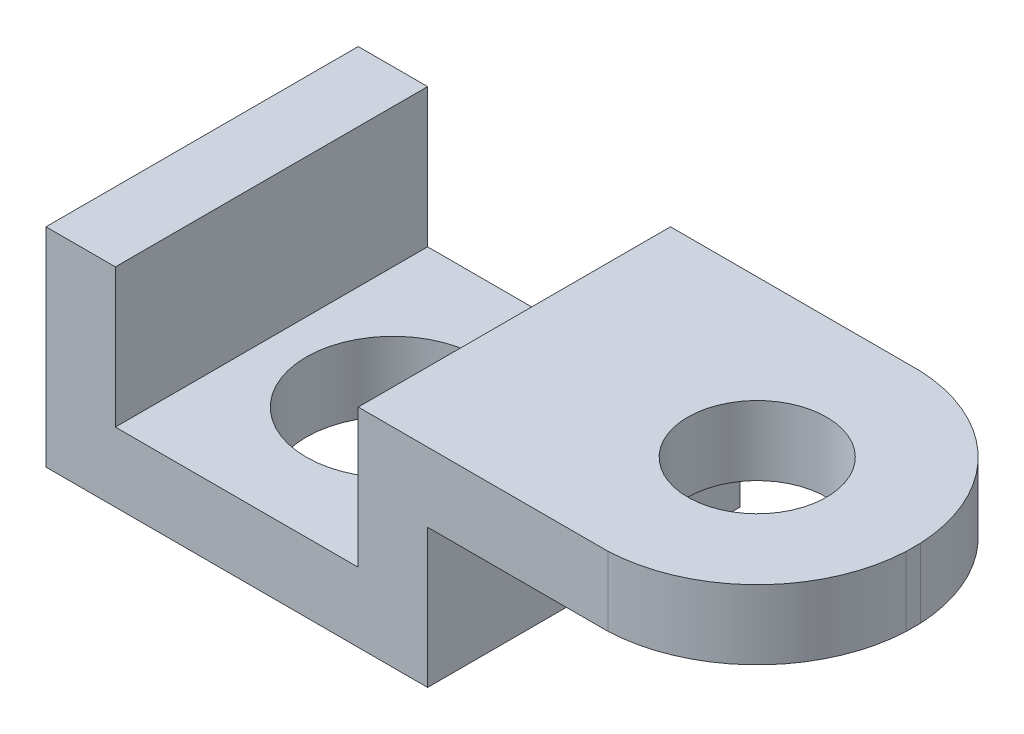
SolidWorks part; units mm, degrees
ref_plane "Front Plane" through (0, 0, 0) normal (0, 0, 1) x (1, 0, 0)
ref_plane "Top Plane" through (0, 0, 0) normal (0, 1, 0) x (1, 0, 0)
ref_plane "Right Plane" through (0, 0, 0) normal (1, 0, 0) x (0, 0, -1)
sketch "Sketch2" plane through (0, 0, 0) normal (0, 0, 1) x (1, 0, 0)
  line L0 (0, 0) -> (69.85, 0)
  line L1 (69.85, 0) -> (69.85, 25.4)
  line L2 (69.85, 25.4) -> (130.175, 25.4)
  line L3 (130.175, 25.4) -> (130.175, 38.1)
  line L4 (130.175, 38.1) -> (57.15, 38.1)
  line L5 (57.15, 38.1) -> (57.15, 12.7)
  line L6 (57.15, 12.7) -> (12.7, 12.7)
  line L7 (12.7, 12.7) -> (12.7, 38.1)
  line L8 (12.7, 38.1) -> (0, 38.1)
  line L9 (0, 38.1) -> (0, 0)
  line L10 (-35.0831, 0) -> (149.1787, 0) construction
  dimension "D1" = 38.1
  dimension "D2" = 12.7
  dimension "D3" = 12.7
  dimension "D4" = 12.7
  dimension "D5" = 12.7
  dimension "D6" = 130.175
  dimension "D7" = 38.1
  dimension "D8" = 69.85
extrude "Boss-Extrude1" add sketch "Sketch2" along normal mid plane 57.15
sketch "Sketch3" plane through (0, 12.7, 0) normal (0, 1, 0) x (1, 0, 0)
  line L0 (-4.144, 0) -> (59.2009, 0) construction
  line L1 (34.925, 45.3012) -> (34.925, -42.2299) construction
  line L2 (0, -28.575) -> (0, 28.575) construction
  circle A0 centre (34.925, 0) radius 15.875
  dimension "D2" = 31.75
  dimension "D1" = 34.925
extrude "Cut-Extrude1" cut sketch "Sketch3" against normal blind 12.7
sketch "Sketch4" plane through (0, 38.1, 0) normal (0, 1, 0) x (1, 0, 0)
  line L0 (-4.6559, 0) -> (34.925, 0) construction
  line L1 (34.925, 0) -> (134.191, 0) construction
  line L2 (101.6, 37.3671) -> (101.6, -39.4146) construction
  line L3 (0, -28.575) -> (0, 28.575) construction
  circle A0 centre (101.6, 0) radius 12.7
  arc A1 (101.6, 28.6044) -> (101.6, -28.6044) centre (101.6, 0) cw
  line M2 (130.175, 28.575) -> (57.15, 28.575)
  line M4 (57.15, -28.575) -> (130.175, -28.575)
  line M5 (130.175, -28.575) -> (130.175, 28.575)
  dimension "D2" = 25.4
  dimension "D3" = 28.6044
  dimension "D1" = 101.6
extrude "Cut-Extrude2" cut sketch "Sketch4" against normal blind 12.7 contours A0 | A1 M2 M5 | A1 M5 M4
